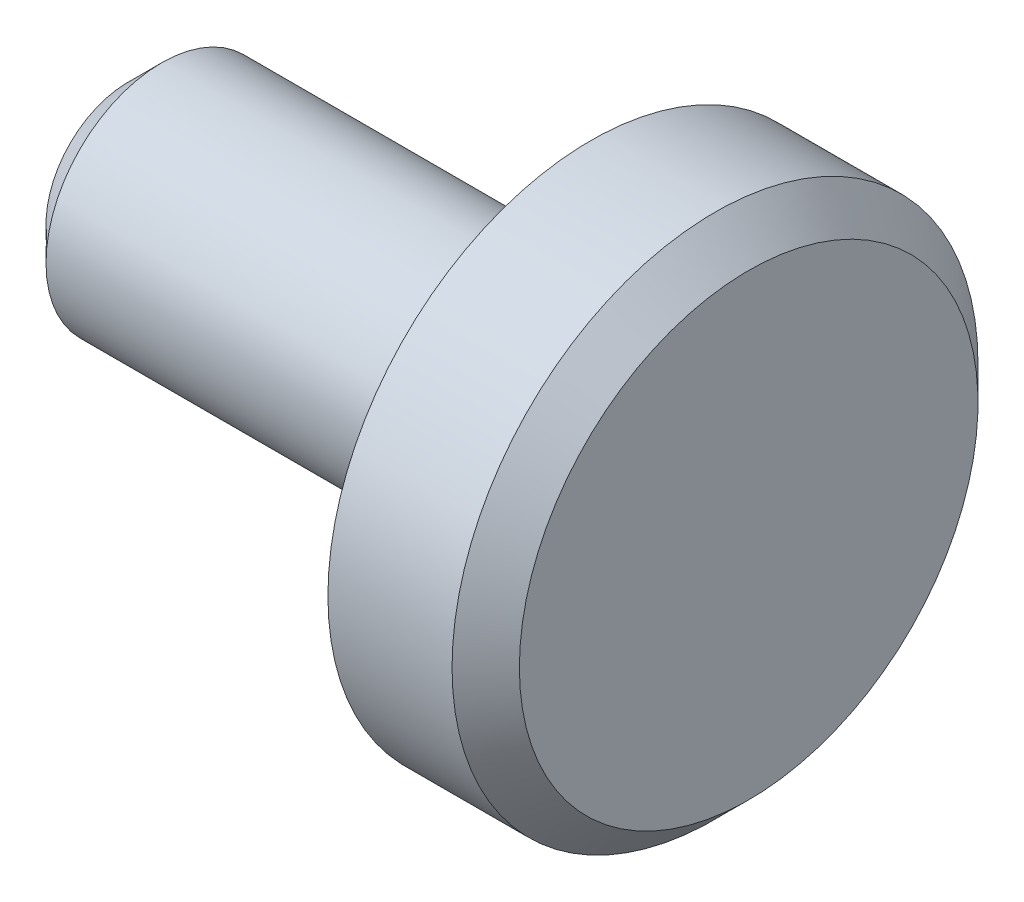
SolidWorks part; units mm, degrees
ref_plane "Front Plane" through (0, 0, 0) normal (0, 0, 1) x (1, 0, 0)
ref_plane "Top Plane" through (0, 0, 0) normal (0, 1, 0) x (1, 0, 0)
ref_plane "Right Plane" through (0, 0, 0) normal (1, 0, 0) x (0, 0, -1)
sketch "Sketch1" plane through (0, 0, 0) normal (0, 0, 1) x (1, 0, 0)
  line L0 (0, 0) -> (0, 6.35)
  line L1 (0, 6.35) -> (-3.81, 6.35)
  line L2 (-3.81, 6.35) -> (-3.81, 2.794)
  line L3 (-3.81, 2.794) -> (-14.986, 2.794)
  line L4 (-14.986, 2.794) -> (-14.986, 0)
  line L5 (-14.986, 0) -> (0, 0)
  dimension "D1" = 3.81
  dimension "D2" = 6.35
  dimension "D3" = 14.986
  dimension "D4" = 2.794
revolve "Revolve1" add sketch "Sketch1" angle 360 about L5
chamfer "Chamfer1" distance 0.8128 angle 45 2 edges at (0, 0, 6.35) (-14.986, 0, 2.794)
